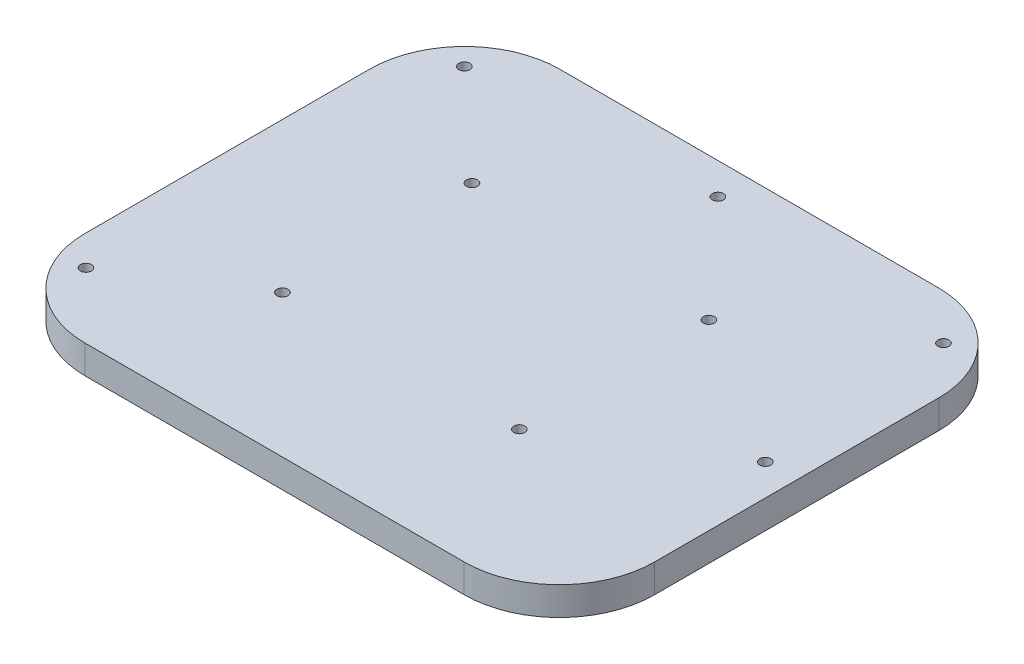
SolidWorks part; units mm, degrees
ref_plane "Front Plane" through (0, 0, 0) normal (0, 0, 1) x (1, 0, 0)
ref_plane "Top Plane" through (0, 0, 0) normal (0, 1, 0) x (1, 0, 0)
ref_plane "Right Plane" through (0, 0, 0) normal (1, 0, 0) x (0, 0, -1)
sketch "Sketch1" plane through (0, 0, 0) normal (0, 1, 0) x (1, 0, 0)
  line L0 (-60, 30) -> (-60, -30)
  line L1 (-40, 50) -> (40, 50)
  line L2 (-40, -50) -> (40, -50)
  line L3 (0, 50) -> (0, -50) construction
  line L4 (-60, 0) -> (94.7381, 0) construction
  line L5 (60, 0) -> (-94.7381, 0) construction
  line L6 (60, 30) -> (60, -30)
  arc A0 (-40, 50) -> (-60, 30) centre (-40, 30) ccw
  arc A1 (-40, -50) -> (-60, -30) centre (-40, -30) cw
  arc A2 (40, -50) -> (60, -30) centre (40, -30) ccw
  arc A3 (40, 50) -> (60, 30) centre (40, 30) cw
  dimension "D1" = 20
  dimension "D2" = 120
  dimension "D3" = 100
extrude "Boss-Extrude1" add sketch "Sketch1" along normal blind 6
sketch "Sketch2" plane through (0, 6, 0) normal (0, 1, 0) x (1, 0, 0)
  line L0 (50.5603, 40.5064) -> (0, 0) construction
  line L1 (-50.5586, 40.5086) -> (0, 0) construction
  line L2 (0, 0) -> (-53.7093, -36.2274) construction
  line L3 (0, 0) -> (-160.8039, 0) construction
  line L4 (0, 0) -> (0, 43.45) construction
  line L5 (0, 0) -> (37.1999, 0) construction
  circle A0 centre (53.475, 0) radius 1.25
  circle A1 centre (-53.7093, -36.2274) radius 1.25
  circle A2 centre (0, 43.45) radius 1.25
  circle A3 centre (50.5603, 40.5064) radius 1.25
  circle A4 centre (-50.5586, 40.5086) radius 1.25
  dimension "D1" = 2.5
  dimension "D2" = 43.45
  dimension "D3" = 64.7851
  dimension "D4" = 38.7
  dimension "D5" = 38.702
  dimension "D6" = 34
  dimension "D7" = 64.7851
  dimension "D8" = 64.7851
  dimension "D9" = 53.475
extrude "Cut-Extrude1" cut sketch "Sketch2" against normal through all
sketch "Sketch3" plane through (0, 6, 0) normal (0, 1, 0) x (1, 0, 0)
  line L0 (0, 0) -> (0, 50) construction
  line L1 (40, 50) -> (-40, 50) construction
  circle A0 centre (-28.45, 20) radius 1.25
  circle A1 centre (21.55, 20) radius 1.25
  circle A2 centre (-28.45, -20) radius 1.25
  circle A3 centre (21.55, -20) radius 1.25
  dimension "D2" = 2.5
  dimension "D1" = 28.45
  dimension "D3" = 50
  dimension "D4" = 40
  dimension "D5" = 30
extrude "Cut-Extrude2" cut sketch "Sketch3" against normal through all
other "Move Face1" face at (21.55, 0, 21.25) face at (52.0711, 3, 42.0711) face at (60, 3, 0) face at (52.0711, 3, -42.0711) face at (0, 3, -50) face at (-52.0711, 3, -42.0711) face at (-60, 3, 0) face at (-52.0711, 3, 42.0711) face at (0, 3, 50) face at (53.475, 0, 1.25) face at (0, 0, -42.2) face at (50.5603, 0, -39.2564) face at (-50.5586, 0, -41.7586) face at (-53.7093, 0, 37.4774) face at (-28.45, 0, -18.75) face at (21.55, 0, -18.75) face at (-28.45, 0, 21.25) parameters "D1"=0.08
